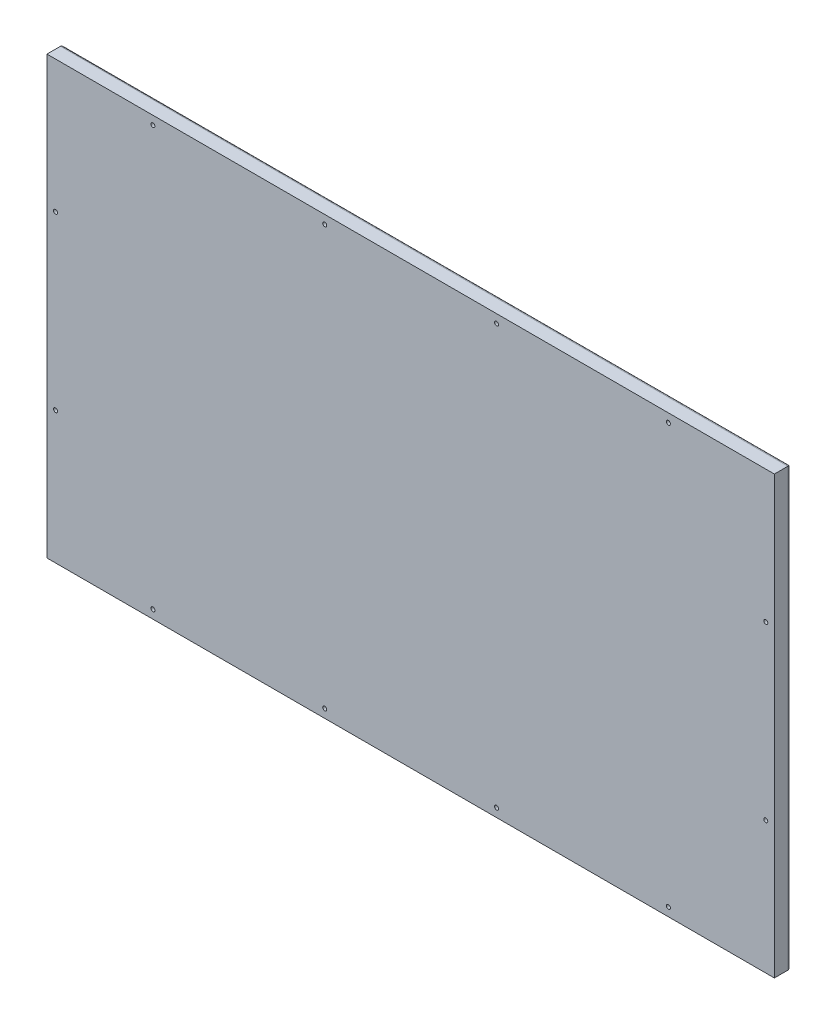
SolidWorks part; units mm, degrees
ref_plane "Front Plane" through (0, 0, 0) normal (0, 0, 1) x (1, 0, 0)
ref_plane "Top Plane" through (0, 0, 0) normal (0, 1, 0) x (1, 0, 0)
ref_plane "Right Plane" through (0, 0, 0) normal (1, 0, 0) x (0, 0, -1)
sketch "Sketch1" plane through (0, 0, 0) normal (0, 0, 1) x (1, 0, 0)
  line L1 (-635, 381) -> (635, 381)
  line L2 (-635, 381) -> (-635, -381)
  line L3 (-635, -381) -> (635, -381)
  line L4 (635, 381) -> (635, -381)
  line L5 (-635, 381) -> (635, -381) construction
  line L6 (-635, -381) -> (635, 381) construction
  point P0 (0, 0)
  dimension "D1" = 1270
  dimension "D2" = 762
extrude "Boss-Extrude1" add sketch "Sketch1" along normal blind 28.575
hole_wizard "CBORE for M6 SHCS1" positions "Sketch5" profile "Sketch4" counterbore size "M6" standard "ANSI Metric" end condition through all
sketch "Sketch5" plane through (0, 0, 0) normal (0, 0, 1) x (1, 0, 0)
  point P0 (-150, 366)
  point P2 (150, 366)
  point P4 (620, 150)
  point P6 (620, -150)
  point P8 (150, -366)
  point P10 (-150, -366)
  point P12 (-620, -150)
  point P14 (-620, 150)
  point P19 (-450, 366)
  point P21 (450, 366)
  point P23 (450, -366)
  point P25 (-450, -366)
  dimension "D1" = 300
  dimension "D2" = 150
  dimension "D3" = 366
  dimension "D4" = 300
  dimension "D5" = 150
  dimension "D6" = 620
  dimension "D7" = 300
  dimension "D8" = 150
  dimension "D9" = 366
  dimension "D10" = 300
  dimension "D11" = 150
  dimension "D12" = 620
  dimension "D13" = 300
  dimension "D14" = 300
sketch "Sketch4" plane through (-150, 366, 0) normal (1, 0, 0) x (0, 1, 0)
  line L0 (0, 0) -> (0, 28.575)
  line L1 (0, 28.575) -> (3.5, 28.575)
  line L3 (3.5, 28.575) -> (3.5, 9.5)
  line L4 (3.5, 9.5) -> (5.5, 9.5)
  line L5 (5.5, 9.5) -> (5.5, 0)
  line L7 (5.5, 0) -> (0, 0)
  line L11 (0, -6.35) -> (0, 107.95) construction
  dimension "Thru Hole Dia." = 7
  dimension "Thru Hole Depth" = 28.575
  dimension "C'Bore Dia." = 11
  dimension "C'Bore Depth" = 9.5
fillet "Fillet1" radius 5 4 edges at (0, -381, 0) (-635, 0, 0) (0, 381, 0) (635, 0, 0)
